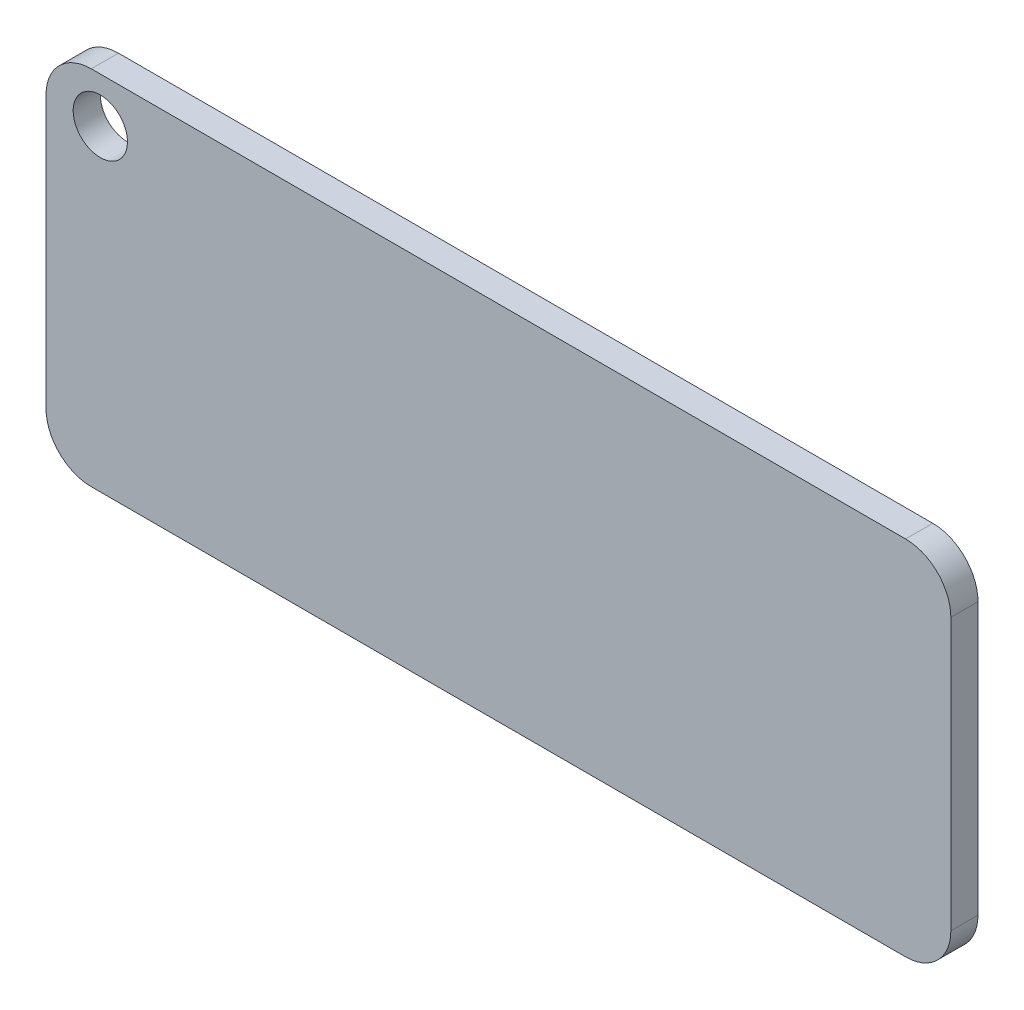
SolidWorks part; units mm, degrees
ref_plane "Front Plane" through (0, 0, 0) normal (0, 0, 1) x (1, 0, 0)
ref_plane "Top Plane" through (0, 0, 0) normal (0, 1, 0) x (1, 0, 0)
ref_plane "Right Plane" through (0, 0, 0) normal (1, 0, 0) x (0, 0, -1)
sketch "Sketch1" plane through (0, 0, 0) normal (0, 0, 1) x (1, 0, 0)
  line L1 (-22.5, -10) -> (22.5, -10)
  line L2 (-25, -7.5) -> (-25, 7.5)
  line L3 (-22.5, 10) -> (22.5, 10)
  line L4 (25, -7.5) -> (25, 7.5)
  line L5 (-25, -10) -> (25, 10) construction
  line L6 (-25, 10) -> (25, -10) construction
  arc A0 (-22.5, -10) -> (-25, -7.5) centre (-22.5, -7.5) cw
  arc A1 (25, -7.5) -> (22.5, -10) centre (22.5, -7.5) cw
  arc A2 (25, 7.5) -> (22.5, 10) centre (22.5, 7.5) ccw
  arc A3 (-22.5, 10) -> (-25, 7.5) centre (-22.5, 7.5) ccw
  point P0 (0, 0)
  dimension "D3" = 2.5
  dimension "D1" = 50
  dimension "D2" = 20
extrude "Boss-Extrude1" add sketch "Sketch1" along normal blind 1.5
sketch "Sketch2" plane through (0, 0, 0) normal (0, 0, -1) x (-1, 0, 0)
  text T0 "F. G. P." font "Century Gothic" height in points 15
extrude "Boss-Extrude2" add sketch "Sketch2" along normal blind 2
sketch "Sketch3" plane through (0, 0, 0) normal (0, 0, -1) x (-1, 0, 0)
  line L0 (25, 7.5) -> (25, -7.5) construction
  line L1 (-22.5, 10) -> (22.5, 10) construction
  circle A0 centre (22, 7.5) radius 1.5
  dimension "D1" = 3
  dimension "D2" = 2.5
extrude "Cut-Extrude2" cut sketch "Sketch3" against normal blind 2
